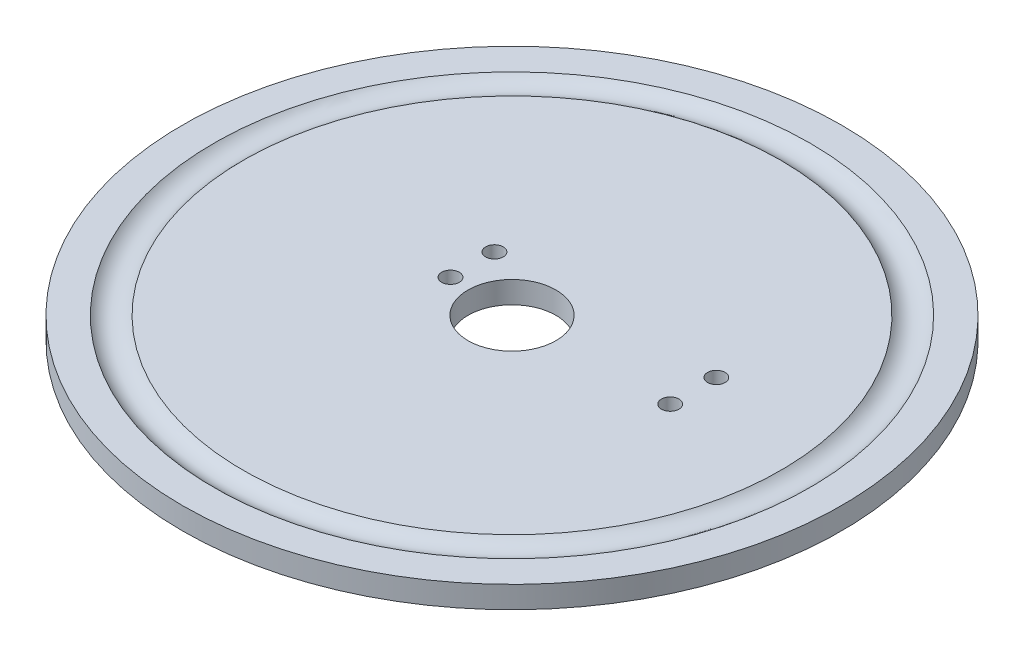
SolidWorks part; units mm, degrees
ref_plane "Alzado" through (0, 0, 0) normal (0, 0, 1) x (1, 0, 0)
ref_plane "Planta" through (0, 0, 0) normal (0, 1, 0) x (1, 0, 0)
ref_plane "Vista lateral" through (0, 0, 0) normal (1, 0, 0) x (0, 0, -1)
sketch "Croquis1" plane through (0, 0, 0) normal (0, 1, 0) x (1, 0, 0)
  circle A0 centre (0, 0) radius 75
  dimension "D1" = 150
extrude "Saliente-Extruir1" add sketch "Croquis1" along normal mid plane 5
sketch "Croquis2" plane through (0, 2.5, 0) normal (0, 1, 0) x (1, 0, 0)
  circle A0 centre (0, 0) radius 10
  dimension "D1" = 20
extrude "Cortar-Extruir1" cut sketch "Croquis2" against normal blind 5
sketch "Croquis4" plane through (0, 2.5, 0) normal (0, 1, 0) x (1, 0, 0)
  circle A0 centre (0, 0) radius 64.5
  dimension "D1" = 129
sketch "Croquis5" plane through (0, 0, 0) normal (1, 0, 0) x (0, 0, -1)
  line L0 (0, 2.5) -> (64.5, 2.5)
  line L1 (64.5, 2.5) -> (-64.5, 2.5) construction
  line L2 (64.5, 2.5) -> (64.5, 5.5)
  circle A0 centre (64.5, 5.5) radius 4.5
  dimension "D3" = 9
  dimension "D1" = 64.5
  dimension "D2" = 3
sweep "Cortar-Barrer1" cut profiles "Croquis5" path "Croquis4"
sketch "Croquis3" plane through (0, 2.5, 0) normal (0, 1, 0) x (1, 0, 0)
  line L0 (0, 0) -> (35.5, 0)
  line L1 (35.5, 0) -> (-14.5, 0)
  line L2 (-14.5, 0) -> (-14.5, 10.5)
  line L3 (-14.5, 10.5) -> (-14.5, 0.5)
  line L4 (35.5, 0) -> (35.5, 11)
  line L5 (35.5, 11) -> (35.5, 0.5)
  circle A0 centre (-14.5, 10.5) radius 2
  circle A1 centre (-14.5, 0.5) radius 2
  circle A2 centre (35.5, 11) radius 2
  circle A3 centre (35.5, 0.5) radius 2
  dimension "D7" = 4
  dimension "D8" = 4
  dimension "D9" = 4
  dimension "D10" = 4
  dimension "D1" = 50
  dimension "D2" = 35.5
  dimension "D3" = 10
  dimension "D4" = 0.5
  dimension "D5" = 0.5
  dimension "D6" = 11
extrude "Cortar-Extruir4" cut sketch "Croquis3" against normal blind 5 contours A0 | A2 | A3 | A1
